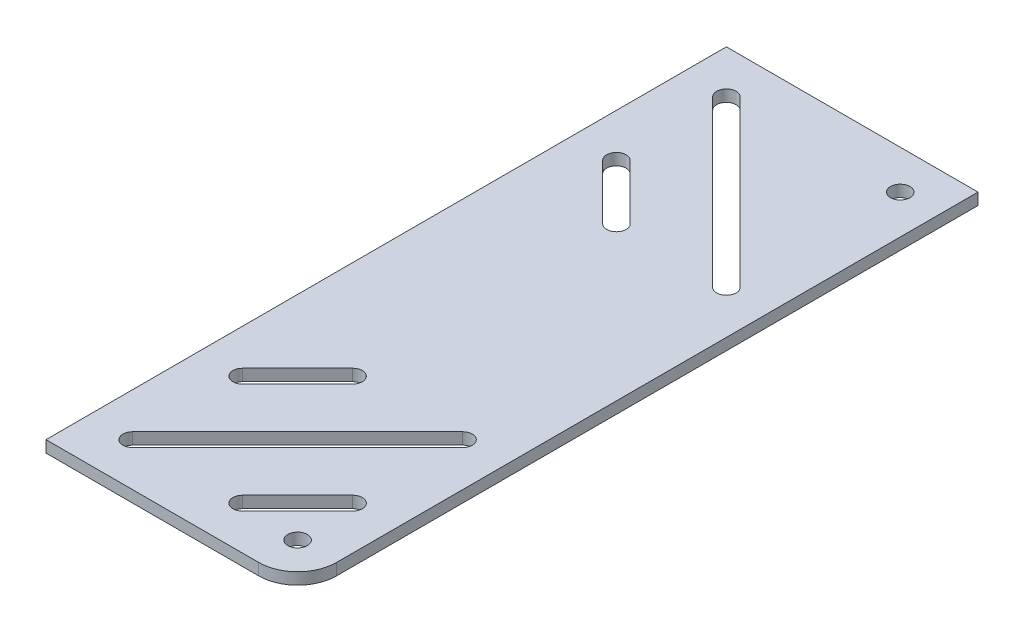
SolidWorks part; units mm, degrees
material "Custom Plastic"
ref_plane "Plan de face" through (0, 0, 0) normal (0, 0, 1) x (1, 0, 0)
ref_plane "Plan de dessus" through (0, 0, 0) normal (0, 1, 0) x (1, 0, 0)
ref_plane "Plan de droite" through (0, 0, 0) normal (1, 0, 0) x (0, 0, -1)
sketch "Esquisse1" plane through (0, 0, 0) normal (0, 1, 0) x (1, 0, 0)
  line L0 (125.7087, 87.5) -> (180.4225, 87.5)
  line L4 (190.4225, 87.5) -> (190.4225, -67.5) construction
  line L7 (190.4225, 77.5) -> (190.4225, -77.5)
  line L8 (180.4225, -87.5) -> (125.7087, -87.5)
  line L10 (125.7087, 87.5) -> (125.7087, -87.5)
  line L11 (180.4225, 87.5) -> (190.4225, 87.5)
  line L12 (180.4225, 87.5) -> (180.4225, 77.5) construction
  line L13 (180.4225, 77.5) -> (190.4225, 77.5) construction
  line L14 (190.4225, -77.5) -> (180.4225, -77.5) construction
  line L15 (180.4225, -77.5) -> (180.4225, -87.5) construction
  line L17 (190.4225, 87.5) -> (190.4225, 77.5)
  line L20 (180.4225, 87.5) -> (180.4225, -87.5) construction
  arc A2 (180.4225, 87.5) -> (190.4225, 77.5) centre (180.4225, 77.5) cw construction
  arc A3 (190.4225, -77.5) -> (180.4225, -87.5) centre (180.4225, -77.5) cw
  circle A6 centre (180.4225, 77.5) radius 2.5
  circle A7 centre (180.4225, -77.5) radius 2.5
  point P22 (180.4225, 0)
  dimension "D4" = 5
  dimension "D1" = 10
  dimension "D2" = 155
extrude "Boss.-Extru.1" add sketch "Esquisse1" along normal blind 3
sketch "Esquisse2" plane through (0, 3, 0) normal (0, 1, 0) x (1, 0, 0)
  line L0 (125.7087, -87.5) -> (190.4225, -22.7862) construction
  line L1 (138.6202, -49.8398) -> (135.0846, -46.3043) construction
  line L2 (190.4225, -77.5) -> (190.4225, 87.5) construction
  line L8 (138.6202, -78.1241) -> (135.0846, -74.5886) construction
  line L9 (177.511, -32.1622) -> (181.0466, -35.6977) construction
  line L10 (138.6202, -78.1241) -> (181.0466, -35.6977)
  line L11 (135.0846, -74.5886) -> (177.511, -32.1622)
  line L12 (159.8334, -56.9109) -> (156.2978, -53.3754) construction
  line L13 (166.9044, -78.1241) -> (163.3689, -74.5886) construction
  line L14 (177.511, -60.4464) -> (181.0466, -63.982) construction
  line L15 (166.9044, -78.1241) -> (181.0466, -63.982)
  line L16 (163.3689, -74.5886) -> (177.511, -60.4464)
  line L17 (173.9755, -71.053) -> (170.44, -67.5175) construction
  line L18 (167.7535, -64.831) -> (160.0777, -57.1552) construction
  line L19 (181.7788, -23.4211) -> (181.7788, 49976.5789) construction
  line L20 (134.3524, -80.9589) -> (134.3524, 49919.0411) construction
  line L21 (125.3963, -78.8563) -> (175.3623, -78.8563) construction
  line L22 (184.9094, -31.4299) -> (134.9433, -31.4299) construction
  line L23 (149.2268, -32.1622) -> (152.7623, -35.6977) construction
  line L24 (138.6202, -49.8398) -> (152.7623, -35.6977)
  line L25 (135.0846, -46.3043) -> (149.2268, -32.1622)
  line L26 (145.6912, -42.7688) -> (142.1557, -39.2332) construction
  line L27 (125.7087, 87.5) -> (190.4225, 22.7862) construction
  line L28 (190.4225, 87.5) -> (125.7087, 87.5) construction
  line L31 (173.9755, 71.053) -> (170.44, 67.5175) construction
  line L32 (177.511, 60.4464) -> (181.0466, 63.982) construction
  line L35 (166.9044, 78.1241) -> (163.3689, 74.5886) construction
  line L38 (159.8334, 56.9109) -> (156.2978, 53.3754) construction
  line L39 (177.511, 32.1622) -> (181.0466, 35.6977) construction
  line L42 (138.6202, 78.1241) -> (135.0846, 74.5886) construction
  line L43 (135.0846, 74.5886) -> (177.511, 32.1622)
  line L44 (138.6202, 78.1241) -> (181.0466, 35.6977)
  line L50 (163.3689, 74.5886) -> (177.511, 60.4464) construction
  line L51 (166.9044, 78.1241) -> (181.0466, 63.982) construction
  line L52 (145.6912, 42.7688) -> (142.1557, 39.2332) construction
  line L53 (149.2268, 32.1622) -> (152.7623, 35.6977) construction
  line L54 (138.6202, 49.8398) -> (135.0846, 46.3043) construction
  line L55 (135.0846, 46.3043) -> (149.2268, 32.1622)
  line L56 (138.6202, 49.8398) -> (152.7623, 35.6977)
  line L57 (84.2748, 31.4299) -> (50084.2748, 31.4299) construction
  line L58 (84.2748, 78.8563) -> (50084.2748, 78.8563) construction
  line L59 (128.208, 25.2855) -> (-26894.0993, -26997.0218) construction
  arc A2 (135.0846, -74.5886) -> (138.6202, -78.1241) centre (136.8524, -76.3563) ccw
  arc A3 (177.511, -32.1622) -> (181.0466, -35.6977) centre (179.2788, -33.9299) cw
  arc A4 (163.3689, -74.5886) -> (166.9044, -78.1241) centre (165.1367, -76.3563) ccw
  arc A5 (177.511, -60.4464) -> (181.0466, -63.982) centre (179.2788, -62.2142) cw
  arc A6 (135.0846, -46.3043) -> (138.6202, -49.8398) centre (136.8524, -48.0721) ccw
  arc A7 (149.2268, -32.1622) -> (152.7623, -35.6977) centre (150.9945, -33.9299) cw
  arc A16 (177.511, 32.1622) -> (181.0466, 35.6977) centre (179.2788, 33.9299) ccw
  arc A17 (135.0846, 74.5886) -> (138.6202, 78.1241) centre (136.8524, 76.3563) cw
  arc A20 (177.511, 60.4464) -> (181.0466, 63.982) centre (179.2788, 62.2142) ccw construction
  arc A21 (163.3689, 74.5886) -> (166.9044, 78.1241) centre (165.1367, 76.3563) cw construction
  arc A22 (149.2268, 32.1622) -> (152.7623, 35.6977) centre (150.9945, 33.9299) ccw
  arc A23 (135.0846, 46.3043) -> (138.6202, 49.8398) centre (136.8524, 48.0721) cw
  point P22 (158.0656, -55.1431)
  point P26 (158.0656, -55.1431)
  point P35 (172.2077, -69.2853)
  point P55 (143.9235, -41.001)
  point P74 (158.0656, 55.1431)
  point P79 (158.0656, 55.1431)
  point P89 (172.2077, 69.2853)
  point P98 (143.9235, 41.001)
  dimension "D3" = 5
  dimension "D4" = 60
  dimension "D5" = 20
  dimension "D6" = 45
  dimension "D7" = 45
extrude "Enlèv. mat.-Extru.1" cut sketch "Esquisse2" against normal through all
